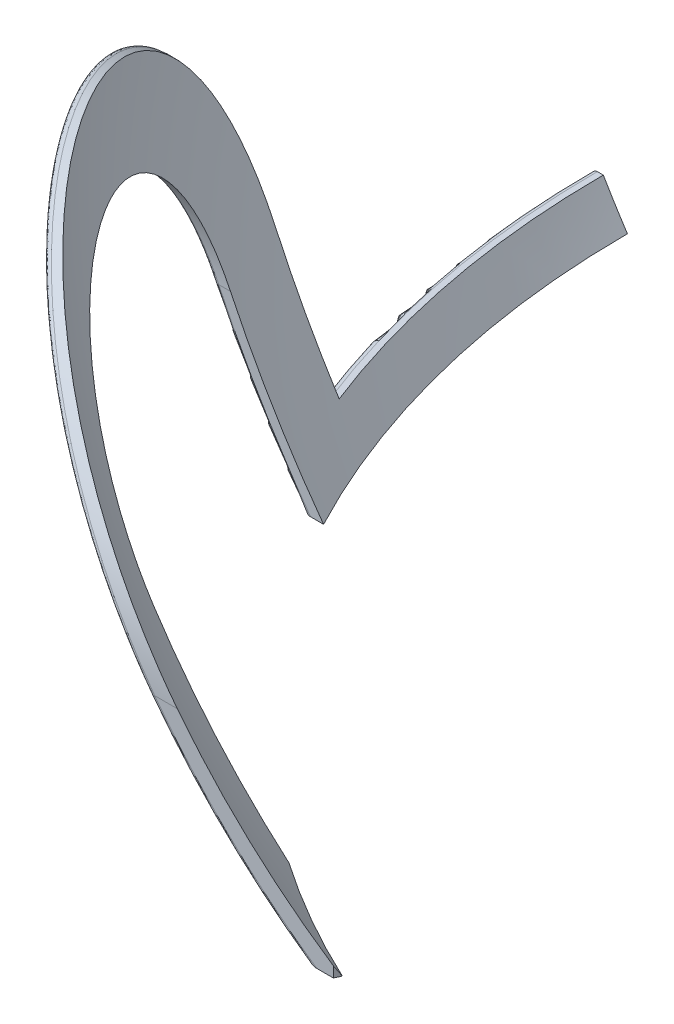
SolidWorks part; units mm, degrees
ref_plane "Front Plane" through (0, 0, 0) normal (0, 0, 1) x (1, 0, 0)
ref_plane "Top Plane" through (0, 0, 0) normal (0, 1, 0) x (1, 0, 0)
ref_plane "Right Plane" through (0, 0, 0) normal (1, 0, 0) x (0, 0, -1)
sketch "Sketch1" plane through (0, 0, 0) normal (0, 0, 1) x (1, 0, 0)
  line L0 (-194.945, -11.7951) -> (-198.7261, -11.7951)
  line L1 (-194.945, -11.7951) -> (-170.4726, -11.7951) construction
  line L2 (-232.4595, 83.4549) -> (-235.6816, 83.4549)
  line L3 (-182.6749, 64.4049) -> (-186.6337, 64.4049) construction
  line L4 (17.78, 127) -> (17.78, 273.6933) construction
  arc A0 (-232.4595, 83.4549) -> (-194.945, -11.7951) centre (17.78, 127) ccw
  arc A1 (-218.7832, 34.513) -> (-205.1291, 5.2316) centre (17.78, 127) ccw construction
  arc A2 (-235.6816, 83.4549) -> (-198.7261, -11.7951) centre (17.78, 127) ccw
  circle A3 centre (17.78, 127) radius 257.175 construction
  circle A4 centre (17.78, 127) radius 254 construction
  spline S0 degree 3 poles (-136.0395, 26.3049) (-137.4308, 28.4303) (-138.8968, 30.4598) (-141.9384, 34.3723) (-143.5146, 36.2548) (-145.9475, 38.9838) (-146.77, 39.8775) (-148.0201, 41.195) (-148.4396, 41.6304) (-149.2786, 42.4882) (-149.6987, 42.9113) (-151.8022, 44.9986) (-153.4944, 46.5794) (-156.8935, 49.576) (-158.6005, 50.9917) (-161.1718, 52.992) (-162.0307, 53.6381) (-163.7522, 54.888) (-164.6162, 55.4926) (-167.1836, 57.2202) (-168.8718, 58.2647) (-172.2032, 60.1352) (-173.8463, 60.9611) (-176.2776, 62.0222) (-177.0825, 62.3461) (-178.2812, 62.7843) (-178.6794, 62.9224) (-179.4729, 63.1821) (-179.8688, 63.3037) (-181.8271, 63.8651) (-183.3362, 64.1679) (-186.2363, 64.4543) (-187.6274, 64.4383) (-189.285, 64.1833) (-189.6126, 64.1203) (-190.2536, 63.9708) (-190.5677, 63.8843) (-191.4905, 63.5884) (-192.0798, 63.3429) (-193.205, 62.7496) (-193.7409, 62.4018) (-194.5019, 61.7967) (-194.7485, 61.581) (-195.2267, 61.1204) (-195.4587, 60.875) (-196.5672, 59.5853) (-197.3011, 58.3475) (-198.0131, 56.5156) (-198.1452, 56.1349) (-198.3877, 55.3433) (-198.498, 54.9324) (-198.7915, 53.6713) (-199.0865, 51.9041) (-199.1907, 49.9658) (-199.1956, 48.4463) (-199.1849, 47.9288) (-199.1386, 46.8713) (-199.1029, 46.3319) (-199.0551, 45.7893) knots 0 0 0 0 0.0625 0.0625 0.125 0.125 0.15625 0.15625 0.171875 0.171875 0.1875 0.1875 0.25 0.25 0.3125 0.3125 0.34375 0.34375 0.375 0.375 0.4375 0.4375 0.5 0.5 0.53125 0.53125 0.546875 0.546875 0.5625 0.5625 0.625 0.625 0.6875 0.6875 0.703125 0.703125 0.71875 0.71875 0.75 0.75 0.78125 0.78125 0.796875 0.796875 0.8125 0.8125 0.875 0.875 0.890625 0.890625 0.90625 0.90625 0.9375 0.96875 0.96875 0.984375 0.984375 1 1 1 1 construction
  point P13 (-186.7367, 64.4049)
  dimension "D2" = 19.05
  dimension "D1" = 3.175
revolve "Revolve1" add sketch "Sketch1" angle 130 mid plane about L4
sketch "Sketch2" plane through (0, 0, 0) normal (1, 0, 0) x (0, 0, -1)
  line L20 (99.06, 26.3049) -> (99.06, -49.8951)
  line L21 (175.26, -49.8951) -> (175.26, 26.3049)
  line L24 (-99.06, -49.8951) -> (-99.06, 26.3049)
  line L25 (-175.26, 26.3049) -> (-175.26, -49.8951)
  line L30 (80.01, 26.3049) -> (80.01, -49.8951)
  line L31 (194.31, -49.8951) -> (194.31, 26.3049)
  line L34 (0, -11.7951) -> (0, 83.4549)
  line L35 (80.01, -2.2701) -> (-99.06, -2.2701)
  line L36 (-196.2212, -11.7951) -> (196.2212, -11.7951)
  line L37 (229.7143, 83.4549) -> (-229.7143, 83.4549)
  line L38 (-196.2212, -11.7951) -> (196.2212, -11.7951)
  line L39 (229.7143, 83.4549) -> (-229.7143, 83.4549)
  arc A20 (175.26, 26.3049) -> (99.06, 26.3049) centre (137.16, 26.3049) ccw
  arc A21 (99.06, -49.8951) -> (175.26, -49.8951) centre (137.16, -49.8951) ccw
  arc A24 (-175.26, -49.8951) -> (-99.06, -49.8951) centre (-137.16, -49.8951) ccw
  arc A25 (-99.06, 26.3049) -> (-175.26, 26.3049) centre (-137.16, 26.3049) ccw
  arc A30 (80.01, -49.8951) -> (194.31, -49.8951) centre (137.16, -49.8951) ccw
  arc A31 (194.31, 26.3049) -> (80.01, 26.3049) centre (137.16, 26.3049) ccw
  ellipse E2 centre (0, 127) end of major axis (0, 384.175) minor radius 233.0797 (-229.7143, 83.4549) -> (-196.2212, -11.7951) ccw
  ellipse E3 centre (0, 127) end of major axis (0, 384.175) minor radius 233.0797 (196.2212, -11.7951) -> (229.7143, 83.4549) ccw
  ellipse E4 centre (0, 127) end of major axis (0, 384.175) minor radius 233.0797 (-229.7143, 83.4549) -> (-196.2212, -11.7951) ccw
  ellipse E5 centre (0, 127) end of major axis (0, 384.175) minor radius 233.0797 (196.2212, -11.7951) -> (229.7143, 83.4549) ccw
  dimension "D3" = 9.525
  dimension "D1" = 19.05
  dimension "D2" = 0
extrude "Cut-Extrude1" cut sketch "Sketch2" against normal through all contours L38 E5 L39 A31 L31 | A31 L39 L34 L35 L30 | L39 E4 L38 L25 A25 L24 L35 L34 | L24 L38 L34 L35 | L24 A25 L25 L38 | L21 A20 L20 L38
fillet "Fillet1" radius 1.27 7 edges at (-186.8216, 6.7325, -99.06) (-199.0058, 61.11, -121.6611) (-99.0624, 5.6309, -194.31) (-205.337, 80.5474, -119.1635) (-126.5453, 6.198, -175.26) (-197.7613, 11.764, -80.01) (-200.7889, -2.2701, -40.6924)
mirror "Mirror1" about plane through (-235.6816, 0, 0) normal (0, 0, -1) of bodies 102
delete or keep bodies "Body-Delete/Keep 1" type delete bodies bodies 102
